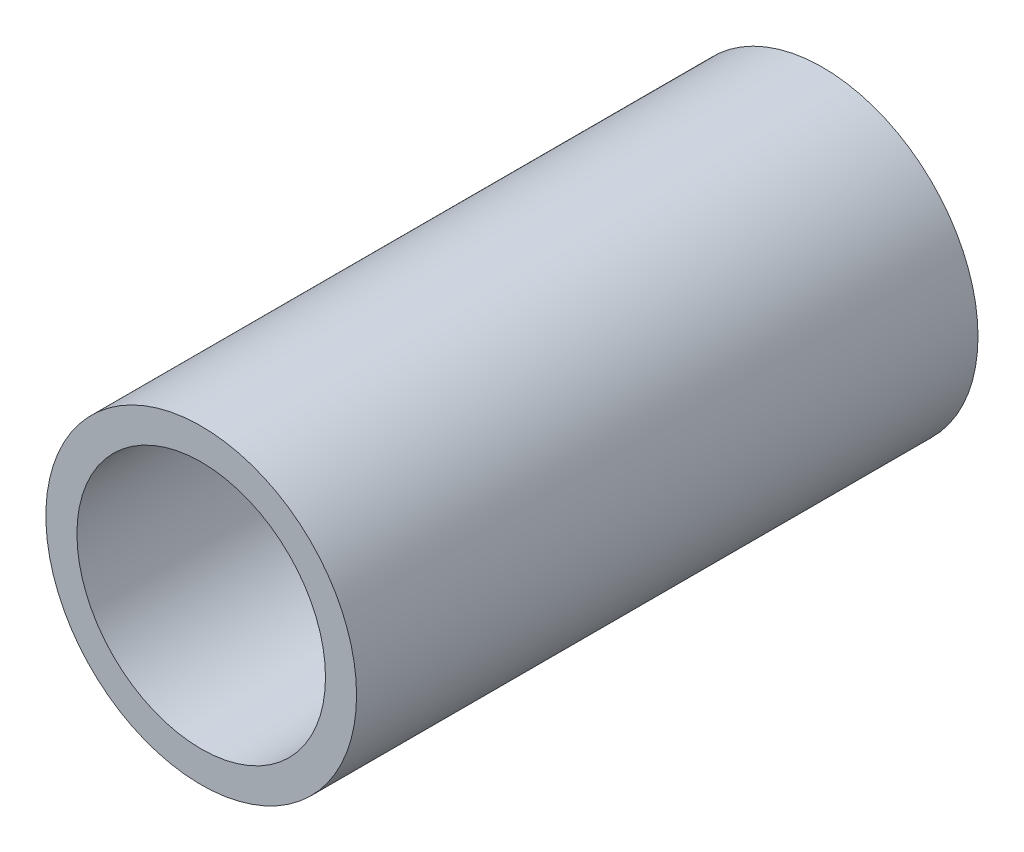
SolidWorks part; units mm, degrees
ref_plane "Alzado" through (0, 0, 0) normal (0, 0, 1) x (1, 0, 0)
ref_plane "Planta" through (0, 0, 0) normal (0, 1, 0) x (1, 0, 0)
ref_plane "Vista lateral" through (0, 0, 0) normal (1, 0, 0) x (0, 0, -1)
sketch "Croquis1" plane through (0, 0, 0) normal (0, 0, 1) x (1, 0, 0)
  circle A0 centre (0, 0) radius 8
  circle A1 centre (0, 0) radius 10
  dimension "D1" = 20
  dimension "D2" = 16
extrude "Saliente-Extruir1" add sketch "Croquis1" along normal blind 40
